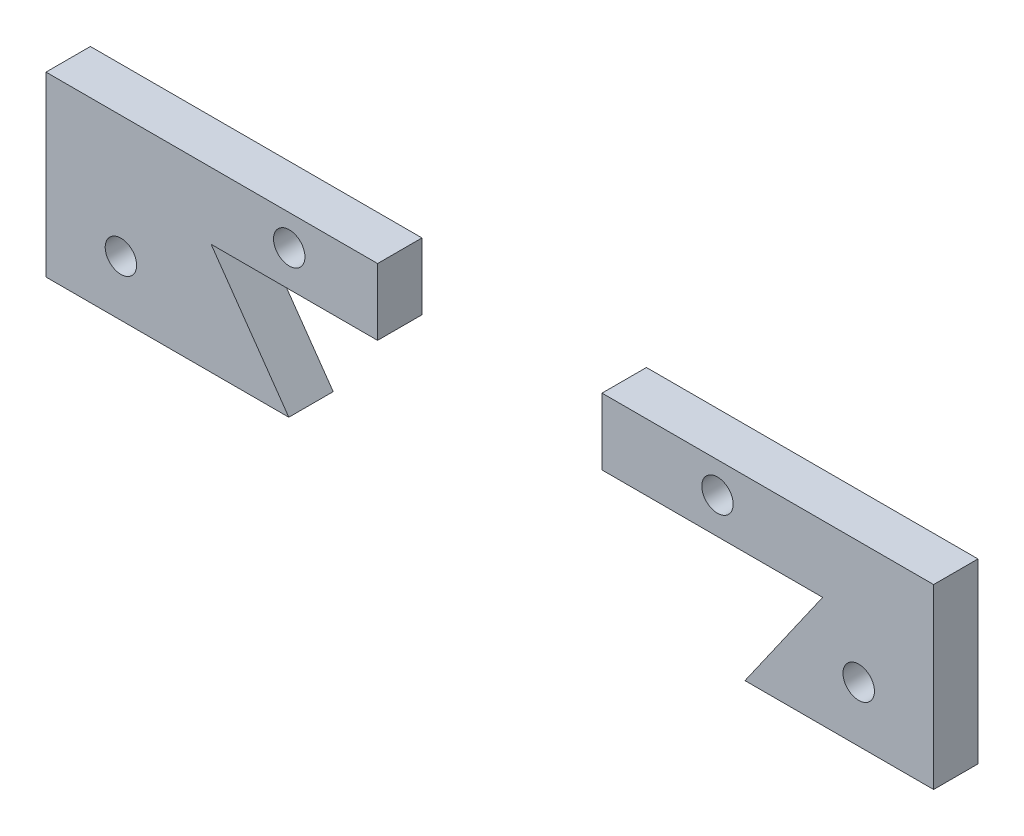
SolidWorks part; units mm, degrees
material "SAE F5 Wool Felt"
ref_plane "Front Plane" through (0, 0, 0) normal (0, 0, 1) x (1, 0, 0)
ref_plane "Top Plane" through (0, 0, 0) normal (0, 1, 0) x (1, 0, 0)
ref_plane "Right Plane" through (0, 0, 0) normal (1, 0, 0) x (0, 0, -1)
sketch "Sketch1" plane through (0, 0, 0) normal (0, 0, 1) x (1, 0, 0)
  line L0 (100.0092, 0) -> (127, 0)
  line L1 (127, 0) -> (127, 28.575) construction
  line L2 (127, 28.575) -> (79.5563, 28.575) construction
  line L3 (79.5563, 28.575) -> (79.5563, 15.875) construction
  line L4 (79.5563, 15.875) -> (111.125, 15.875)
  line L5 (111.125, 15.875) -> (100.0092, 0)
  line L6 (0, 0) -> (0, 25.4)
  line L7 (0, 25.4) -> (47.4437, 25.4)
  line L8 (127, 28.575) -> (0, 28.575)
  line L9 (0, 28.575) -> (0, 0)
  line L10 (0, 0) -> (26.9908, 0)
  line L11 (26.9908, 0) -> (15.875, 15.875)
  line L12 (15.875, 15.875) -> (111.125, 15.875)
  line L13 (111.125, 15.875) -> (100.0092, 0)
  line L14 (100.0092, 0) -> (127, 0)
  line L15 (127, 0) -> (127, 28.575)
  line L16 (127, 28.575) -> (0, 28.575) construction
  line L17 (0, 28.575) -> (0, 0) construction
  line L18 (0, 0) -> (26.9908, 0) construction
  line L19 (26.9908, 0) -> (15.875, 15.875) construction
  line L20 (15.875, 15.875) -> (111.125, 15.875) construction
  line L21 (111.125, 15.875) -> (100.0092, 0) construction
  line L22 (100.0092, 0) -> (127, 0) construction
  line L23 (127, 0) -> (127, 28.575) construction
  line L24 (47.4437, 25.4) -> (47.4437, 15.875)
  line L25 (127, 0) -> (127, 25.4)
  line L26 (127, 25.4) -> (79.5563, 25.4)
  line L27 (79.5563, 25.4) -> (79.5563, 15.875)
  line L28 (79.5563, -3.175) -> (47.4437, -3.175)
  line L29 (47.4437, -3.175) -> (47.4437, 15.875)
  line L30 (47.4437, 15.875) -> (23.6269, 15.875)
  line L31 (23.6269, 15.875) -> (34.7427, 0)
  line L32 (34.7427, 0) -> (0, 0)
  line L33 (0, 0) -> (0, -15.875)
  line L34 (0, -15.875) -> (127, -15.875)
  line L35 (127, -15.875) -> (127, 0)
  line L36 (127, 0) -> (100.0092, 0)
  line L37 (100.0092, 0) -> (111.125, 15.875)
  line L38 (111.125, 15.875) -> (79.5563, 15.875)
  line L39 (79.5563, 15.875) -> (79.5563, -3.175)
  line L40 (79.5563, -3.175) -> (47.4437, -3.175) construction
  line L41 (47.4437, -3.175) -> (47.4437, 15.875) construction
  line L42 (47.4437, 15.875) -> (23.6269, 15.875) construction
  line L43 (23.6269, 15.875) -> (34.7427, 0) construction
  line L44 (34.7427, 0) -> (0, 0) construction
  line L45 (0, 0) -> (0, -15.875) construction
  line L46 (0, -15.875) -> (127, -15.875) construction
  line L47 (127, -15.875) -> (127, 0) construction
  line L48 (127, 0) -> (100.0092, 0) construction
  line L49 (100.0092, 0) -> (111.125, 15.875) construction
  line L50 (111.125, 15.875) -> (79.5563, 15.875) construction
  line L51 (79.5563, 15.875) -> (79.5563, -3.175) construction
  line L58 (0, 0) -> (34.7427, 0)
  line L59 (34.7427, 0) -> (23.6269, 15.875)
  line L60 (23.6269, 15.875) -> (47.4437, 15.875)
  line L61 (47.4437, 15.875) -> (47.4437, 28.575) construction
  line L62 (47.4437, 28.575) -> (0, 28.575) construction
  line L63 (0, 28.575) -> (0, 0) construction
  dimension "D3" = 25.4
  dimension "D1" = 0
  dimension "D2" = 0
extrude "Boss-Extrude1" add sketch "Sketch1" along normal blind 6.35
hole_wizard "#8 Clearance Hole1" positions "Sketch2" profile "Sketch3" hole size "#8" standard "ANSI Inch" end condition through all
sketch "Sketch2" plane through (0, -15.875, 6.35) normal (0, 0, 1) x (1, 0, 0)
  line L0 (34.8034, 41.275) -> (34.8034, 32.512) construction
  line L3 (96.0726, 41.275) -> (96.0726, 32.512) construction
  line L6 (111.125, 31.75) -> (127, 31.75) construction
  line L7 (15.875, 31.75) -> (0, 31.75) construction
  line L8 (7.9375, 31.75) -> (13.4954, 15.875) construction
  line L9 (119.0625, 31.75) -> (113.5046, 15.875) construction
  line L22 (127, 44.45) -> (0, 44.45) construction
  line L23 (0, 44.45) -> (0, 15.875) construction
  line L24 (0, 15.875) -> (26.9908, 15.875) construction
  line L25 (26.9908, 15.875) -> (15.875, 31.75) construction
  line L26 (15.875, 31.75) -> (111.125, 31.75) construction
  line L27 (111.125, 31.75) -> (100.0092, 15.875) construction
  line L28 (100.0092, 15.875) -> (127, 15.875) construction
  line L29 (127, 15.875) -> (127, 44.45) construction
  point P0 (10.7164, 23.8125)
  point P1 (34.8034, 36.8935)
  point P2 (96.0726, 36.8935)
  point P3 (116.2836, 23.8125)
sketch "Sketch3" plane through (10.7164, 7.9375, 6.35) normal (1, 0, 0) x (0, -1, 0)
  line L0 (0, 0) -> (0, 6.35)
  line L1 (0, 6.35) -> (2.2479, 6.35)
  line L2 (2.2479, 6.35) -> (2.2479, 0)
  line L3 (2.2479, 0) -> (0, 0)
  line L4 (0, -6.35) -> (0, 107.95) construction
  dimension "Thru Hole Dia." = 4.4958
  dimension "Thru Hole Depth" = 6.35
equation "\"dovetail-angle\" = 55"
equation "\"dovetail-stock-width\" = 5"
equation "\"dovetail-stock-height\" = 1.25"
equation "\"dovetail-depth\" = 0.5 * \"dovetail-stock-height\""
equation "\"dovetail-throat-width\" = \"dovetail-stock-width\" - (2 * \"dovetail-depth\")"
equation "\"delta-x\" = 6"
equation "\"delta-y\" = 3"
equation "\"gib-thickness\" = 0.25"
equation "\"x-slide-length\" = \"dovetail-stock-width\" + \"delta-x\""
equation "\"y-slide-length\" = \"dovetail-stock-width\" + \"delta-y\""
equation "\"dog-point-diam\" = .149"
equation "\"dog-point-length\" = .067"
equation "\"dovetail-double-height\" = 2 * \"dovetail-depth\" + 0.5"
equation "\"acme-major-diam\" = .5"
equation "\"acme-pitch-diam\" = 0.45"
equation "\"acme-minor-diam\" = 0.4"
equation "\"acme-nut-od\" = 1.47"
equation "\"acme-nut-length\" = 1"
equation "\"acme-nut-trim-height\" = .75"
equation "\"screw-bearing-od\" = 0.5"
equation "\"screw-bearing-length\" = .25"
equation "\"screw-bearing-id\" = .375"
equation "\"end-plate-thickness\" = \"screw-bearing-length\""
equation "\"screw-add-length\" = 2 * \"end-plate-thickness\" + 1 + 0.5"
equation "\"x-screw-length\" = \"x-slide-length\" + \"screw-add-length\""
equation "\"y-screw-length\" = \"y-slide-length\" + \"screw-add-length\""
equation "\"acme-nut-mount-hole-space-horz\" = 0.82"
equation "\"acme-nut-mount-hole-space-vert\" = 0.5 * \"acme-nut-length\""
equation "\"vise-hole-center-dist\" = 6.75"
equation "\"wiper_plate_clearance\" = .03"
